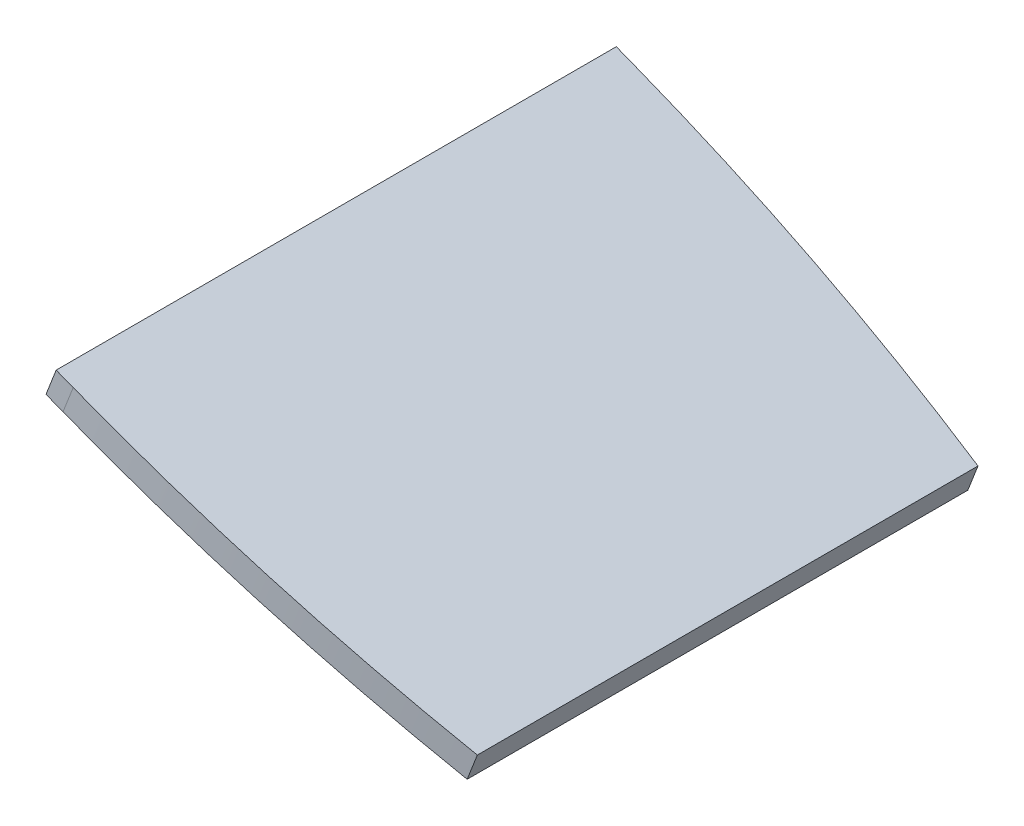
SolidWorks part; units mm, degrees
ref_plane "Front Plane" through (0, 0, 0) normal (0, 0, 1) x (1, 0, 0)
ref_plane "Top Plane" through (0, 0, 0) normal (0, 1, 0) x (1, 0, 0)
ref_plane "Right Plane" through (0, 0, 0) normal (1, 0, 0) x (0, 0, -1)
sketch "Sketch2" plane through (-5.1895, -13.3184, 0) normal (0.3631, 0.9318, 0) x (0.9318, -0.3631, 0)
  line L4 (-113.9478, -6.6627) -> (-115.6039, -6.6627)
  line L5 (-115.6039, -6.6627) -> (-115.6039, -57.4627)
  line L6 (-115.6039, -57.4627) -> (-113.9478, -57.4627)
  line L7 (-77.5039, -54.7665) -> (-77.5039, -9.3589)
  line L8 (-113.9478, -6.6627) -> (-115.6039, -6.6627)
  line L9 (-115.6039, -6.6627) -> (-115.6039, -57.4627)
  line L10 (-115.6039, -57.4627) -> (-113.9478, -57.4627)
  line L11 (-77.5039, -54.7665) -> (-77.5039, -9.3589)
  arc A2 (-113.9478, -57.4627) -> (-77.5039, -54.7665) centre (-113.9478, 190.1873) ccw
  arc A3 (-77.5039, -9.3589) -> (-113.9478, -6.6627) centre (-113.9478, -254.3127) ccw
  arc A4 (-113.9478, -57.4627) -> (-77.5039, -54.7665) centre (-113.9478, 190.1873) ccw
  arc A5 (-77.5039, -9.3589) -> (-113.9478, -6.6627) centre (-113.9478, -254.3127) ccw
  dimension "D1" = 0
extrude "Boss-Extrude1" add sketch "Sketch2" along normal blind 2.54
